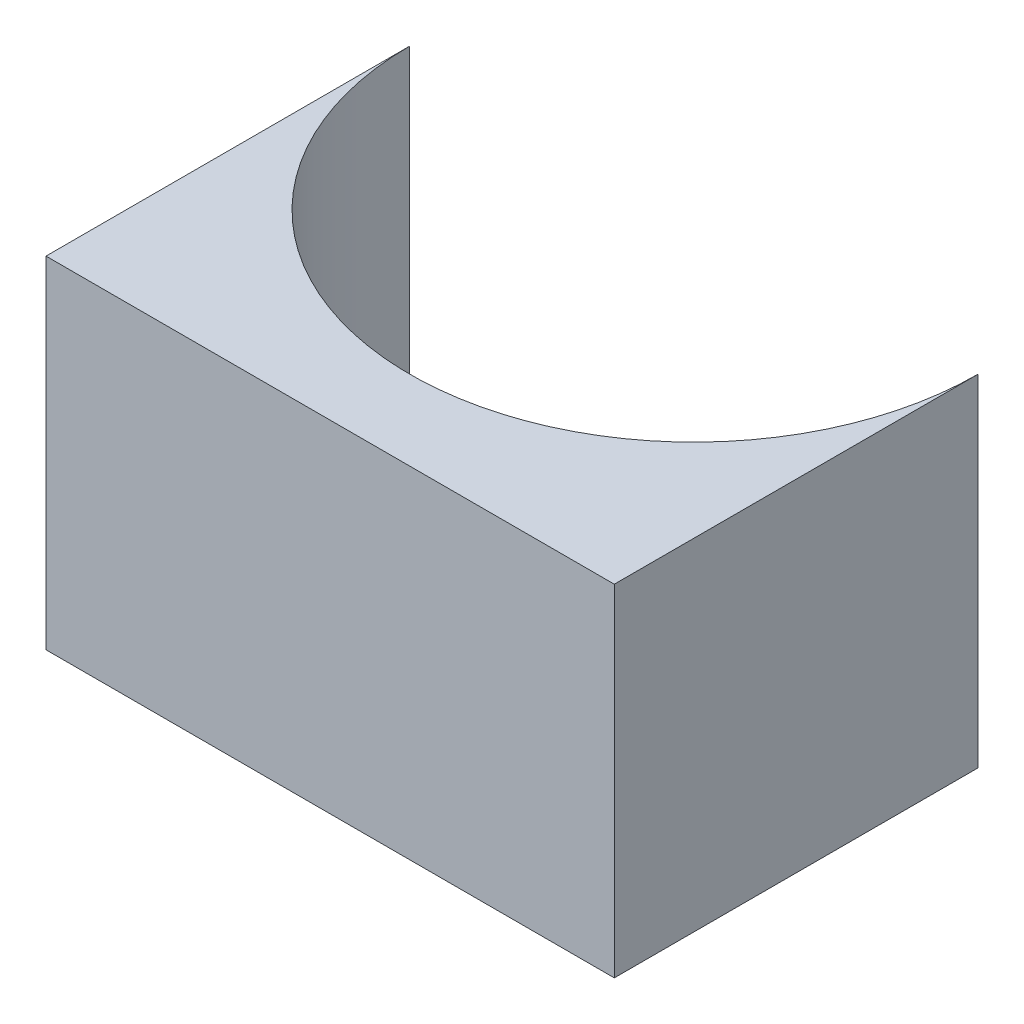
SolidWorks part; units mm, degrees
ref_plane "Front Plane" through (0, 0, 0) normal (0, 0, 1) x (1, 0, 0)
ref_plane "Top Plane" through (0, 0, 0) normal (0, 1, 0) x (1, 0, 0)
ref_plane "Right Plane" through (0, 0, 0) normal (1, 0, 0) x (0, 0, -1)
sketch "Sketch1" plane through (0, 0, 0) normal (0, 1, 0) x (1, 0, 0)
  line L1 (-37.5, -16) -> (12.5, -16)
  line L2 (-37.5, -16) -> (-37.5, 16)
  line L4 (12.5, -16) -> (12.5, 16)
  line L5 (-37.5, -16) -> (-19.0481, -8.1272) construction
  line L6 (2.8911, -3.7006) -> (12.5, -16) construction
  arc A0 (-37.5, 16) -> (12.5, 16) centre (-12.5, 16) ccw
  point P0 (0, 0)
  dimension "D1" = 32
  dimension "D2" = 50
extrude "Boss-Extrude1" add sketch "Sketch1" along normal blind 30
